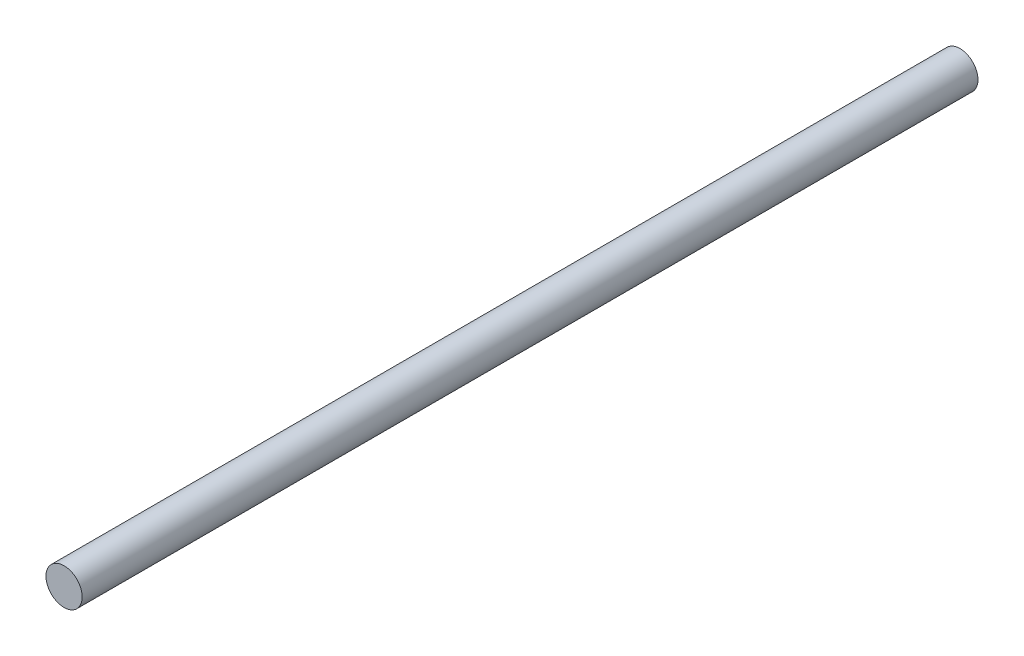
SolidWorks part; units mm, degrees
ref_plane "前视基准面" through (0, 0, 0) normal (0, 0, 1) x (1, 0, 0)
ref_plane "上视基准面" through (0, 0, 0) normal (0, 1, 0) x (1, 0, 0)
ref_plane "右视基准面" through (0, 0, 0) normal (1, 0, 0) x (0, 0, -1)
sketch "草图1" plane through (0, 0, 0) normal (0, 0, 1) x (1, 0, 0)
  circle A0 centre (0, 0) radius 10
extrude "凸台-拉伸2" add sketch "草图1" along normal blind 495
